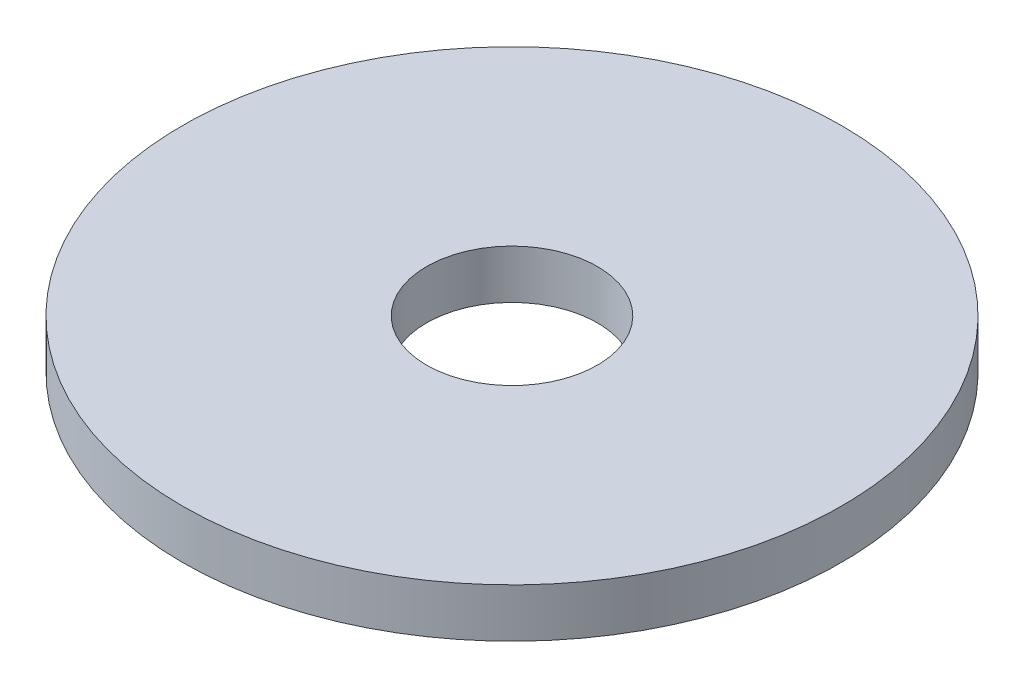
SolidWorks part; units mm, degrees
ref_plane "Front Plane" through (0, 0, 0) normal (0, 0, 1) x (1, 0, 0)
ref_plane "Top Plane" through (0, 0, 0) normal (0, 1, 0) x (1, 0, 0)
ref_plane "Right Plane" through (0, 0, 0) normal (1, 0, 0) x (0, 0, -1)
sketch "Sketch1" plane through (0, 0, 0) normal (0, 1, 0) x (1, 0, 0)
  circle A0 centre (0, 0) radius 1.75
  circle A1 centre (0, 0) radius 6.75
  dimension "D1" = 3.5
  dimension "D2" = 5
extrude "Boss-Extrude1" add sketch "Sketch1" along normal blind 1
